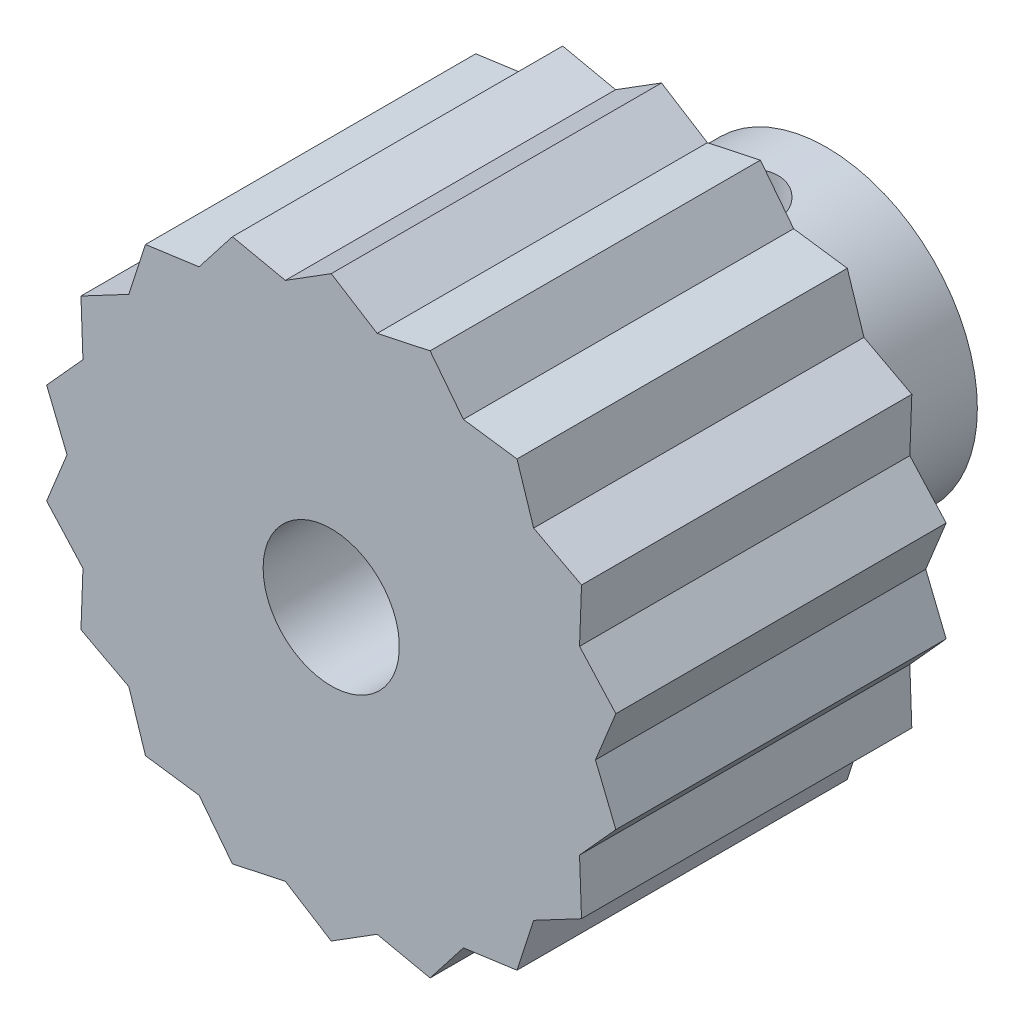
SolidWorks part; units mm, degrees
ref_plane "Alzado" through (0, 0, 0) normal (0, 0, 1) x (1, 0, 0)
ref_plane "Planta" through (0, 0, 0) normal (0, 1, 0) x (1, 0, 0)
ref_plane "Vista lateral" through (0, 0, 0) normal (1, 0, 0) x (0, 0, -1)
sketch "Croquis1" plane through (0, 0, 0) normal (0, 0, 1) x (1, 0, 0)
  circle A0 centre (0, 0) radius 17.5
  dimension "D1" = 35
extrude "Saliente-Extruir1" add sketch "Croquis1" along normal blind 20
sketch "Croquis2" plane through (0, 0, 0) normal (0, 0, -1) x (-1, 0, 0)
  circle A0 centre (0, 0) radius 9.125
  circle A1 centre (0, 0) radius 4.125
  dimension "D1" = 8.25
  dimension "D2" = 5
extrude "Saliente-Extruir2" add sketch "Croquis2" along normal blind 10
sketch "Croquis3" plane through (0, 0, 20) normal (0, 0, 1) x (1, 0, 0)
  line L0 (0, 17.5) -> (0, 0) construction
  line L1 (2.7784, 15.7569) -> (0, 0) construction
  line L2 (0, 17.5) -> (2.7784, 15.7569)
  line L3 (2.7784, 15.7569) -> (5.9854, 16.4446)
  line L4 (8, 13.8564) -> (11.2488, 13.4058)
  line L5 (5.9854, 16.4446) -> (8, 13.8564)
  line L6 (12.2567, 10.2846) -> (15.1554, 8.75)
  line L7 (11.2488, 13.4058) -> (12.2567, 10.2846)
  line L8 (15.0351, 5.4723) -> (17.2341, 3.0388)
  line L9 (15.1554, 8.75) -> (15.0351, 5.4723)
  line L10 (16, 0) -> (17.2341, -3.0388)
  line L11 (17.2341, 3.0388) -> (16, 0)
  line L12 (15.0351, -5.4723) -> (15.1554, -8.75)
  line L13 (17.2341, -3.0388) -> (15.0351, -5.4723)
  line L14 (12.2567, -10.2846) -> (11.2488, -13.4058)
  line L15 (15.1554, -8.75) -> (12.2567, -10.2846)
  line L16 (8, -13.8564) -> (5.9854, -16.4446)
  line L17 (11.2488, -13.4058) -> (8, -13.8564)
  line L18 (2.7784, -15.7569) -> (0, -17.5)
  line L19 (5.9854, -16.4446) -> (2.7784, -15.7569)
  line L20 (-2.7784, -15.7569) -> (-5.9854, -16.4446)
  line L21 (0, -17.5) -> (-2.7784, -15.7569)
  line L22 (-8, -13.8564) -> (-11.2488, -13.4058)
  line L23 (-5.9854, -16.4446) -> (-8, -13.8564)
  line L24 (-12.2567, -10.2846) -> (-15.1554, -8.75)
  line L25 (-11.2488, -13.4058) -> (-12.2567, -10.2846)
  line L26 (-15.0351, -5.4723) -> (-17.2341, -3.0388)
  line L27 (-15.1554, -8.75) -> (-15.0351, -5.4723)
  line L28 (-16, 0) -> (-17.2341, 3.0388)
  line L29 (-17.2341, -3.0388) -> (-16, 0)
  line L30 (-15.0351, 5.4723) -> (-15.1554, 8.75)
  line L31 (-17.2341, 3.0388) -> (-15.0351, 5.4723)
  line L32 (-12.2567, 10.2846) -> (-11.2488, 13.4058)
  line L33 (-15.1554, 8.75) -> (-12.2567, 10.2846)
  line L34 (-8, 13.8564) -> (-5.9854, 16.4446)
  line L35 (-11.2488, 13.4058) -> (-8, 13.8564)
  line L36 (-2.7784, 15.7569) -> (0, 17.5)
  line L37 (-5.9854, 16.4446) -> (-2.7784, 15.7569)
  circle A0 centre (0, 0) radius 17.5 construction
  circle A2 centre (0, 0) radius 19
  point P62 (0, 0)
  dimension "D4" = 38
  dimension "D1" = 10
  dimension "D2" = 16
  dimension "D3" = 18
extrude "Cortar-Extruir1" cut sketch "Croquis3" against normal up to next
sketch "Croquis4" plane through (0, 0, 0) normal (0, 1, 0) x (1, 0, 0)
  line L0 (0, 0) -> (0, 10) construction
  line L1 (9.125, 10) -> (-9.125, 10) construction
  circle A1 centre (0, 5) radius 2.05
  dimension "D2" = 4.1
  dimension "D1" = 5
extrude "Cortar-Extruir2" cut sketch "Croquis4" against normal through all both and the other way through all
sketch "Croquis5" plane through (0, 0, 0) normal (0, 0, -1) x (-1, 0, 0)
  circle A1 centre (0, 0) radius 4.125
  circle A2 centre (0, 0) radius 4.125
  dimension "D1" = 0
extrude "Cortar-Extruir3" cut sketch "Croquis5" against normal through all
